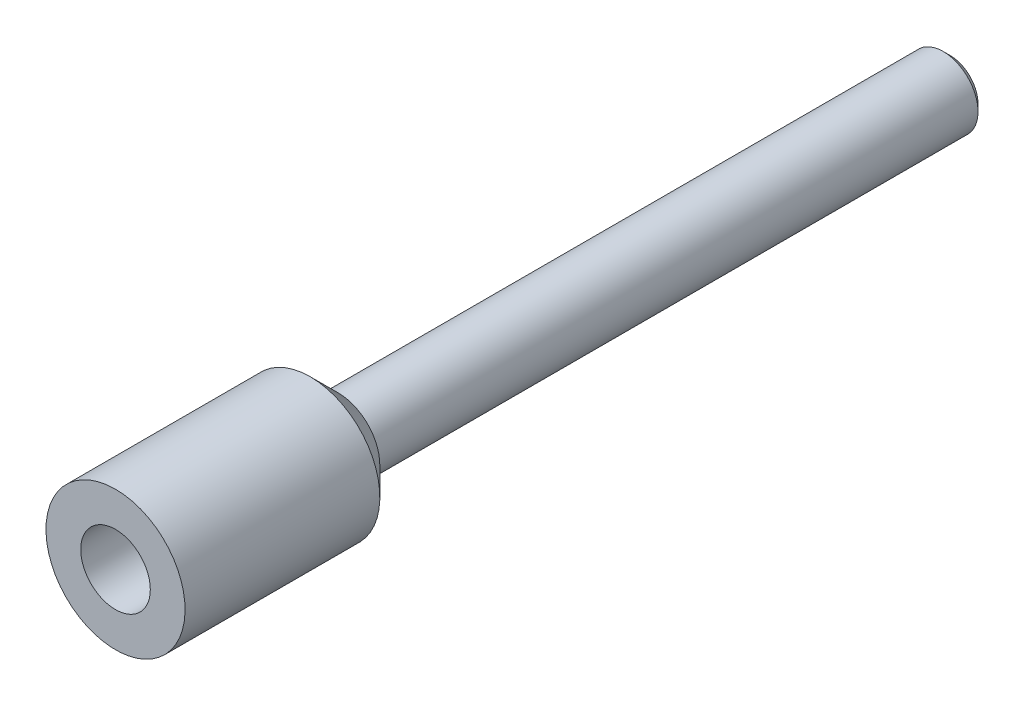
SolidWorks part; units mm, degrees
ref_plane "정면" through (0, 0, 0) normal (0, 0, 1) x (1, 0, 0)
ref_plane "윗면" through (0, 0, 0) normal (0, 1, 0) x (1, 0, 0)
ref_plane "우측면" through (0, 0, 0) normal (1, 0, 0) x (0, 0, -1)
sketch "스케치1" plane through (0, 0, 0) normal (1, 0, 0) x (0, 0, -1)
  line L0 (0, 0) -> (0, 5)
  line L1 (0, 5) -> (14, 5)
  line L2 (16, 2.5) -> (16, 3)
  line L3 (16, 3) -> (14, 5)
  line L5 (16, 2.5) -> (60, 2.5)
  line L6 (60, 2.5) -> (60, 0)
  line L7 (60, 0) -> (0, 0)
  dimension "D1" = 60
  dimension "D2" = 2.5
  dimension "D3" = 0.5
  dimension "D4" = 135
  dimension "D5" = 2
  dimension "D6" = 5
  dimension "D7" = 14
revolve "회전1" add sketch "스케치1" angle 360 about L7
hole_wizard "M6x1.0 나사 구멍1" positions "스케치3" profile "스케치4" tap size "M6x1.0" standard "Ansi Metric"
sketch "스케치3" plane through (0, 0, 0) normal (0, 0, 1) x (1, 0, 0)
  point P0 (0, 0)
sketch "스케치4" plane through (0, 0, 0) normal (1, 0, 0) x (0, -1, 0)
  line L0 (0, 0) -> (0, 13.5022)
  line L1 (0, 13.5022) -> (2.5, 12)
  line L2 (2.5, 12) -> (2.5, 0)
  line L5 (2.5, 0) -> (0, 0)
  line L10 (0, 13.5022) -> (-2.5, 12) construction
  line L11 (0, -6.35) -> (0, 107.95) construction
  dimension "탭 드릴 지름" = 5
  dimension "탭 드릴 깊이" = 12
  dimension "드릴 각도" = 118
cosmetic thread "구멍 나사산1"
chamfer "모따기1" distance 0.5 angle 45 1 edges at (0, 2.5, -60)
